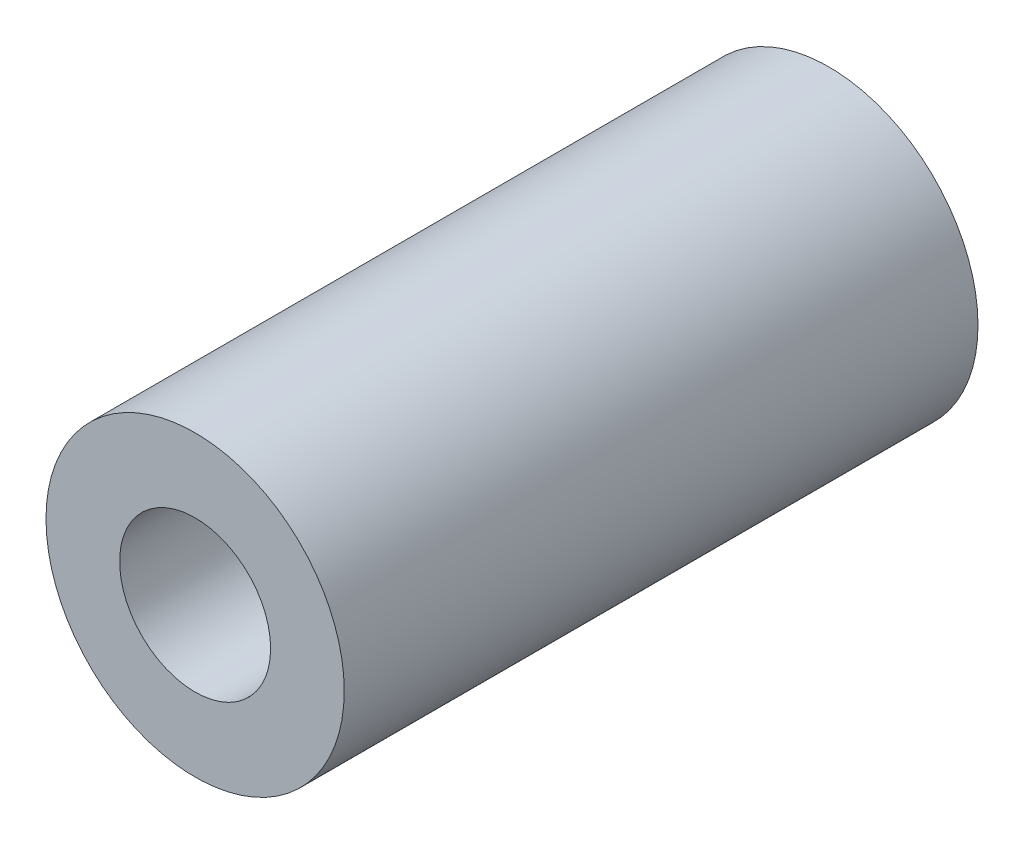
SolidWorks part; units mm, degrees
ref_plane "Front Plane" through (0, 0, 0) normal (0, 0, 1) x (1, 0, 0)
ref_plane "Top Plane" through (0, 0, 0) normal (0, 1, 0) x (1, 0, 0)
ref_plane "Right Plane" through (0, 0, 0) normal (1, 0, 0) x (0, 0, -1)
sketch "S01 - Solid post blank - 16 mm" plane through (0, 0, 0) normal (0, 0, 1) x (1, 0, 0)
  circle A0 centre (0, 0) radius 8
extrude "01 - Solid post blank - 16 mm" add sketch "S01 - Solid post blank - 16 mm" along normal blind 34
sketch "S02 - Rear M6 heat-set insert seat" plane through (0, 0, 0) normal (0, 0, 1) x (1, 0, 0)
  circle A0 centre (0, 0) radius 4.05
extrude "02 - Rear M6 heat-set insert seat" cut sketch "S02 - Rear M6 heat-set insert seat" along normal blind 14.35 from offset 0.1 offset against normal yes
sketch "S03 - Front M6 heat-set insert seat" plane through (0, 0, 0) normal (0, 0, 1) x (1, 0, 0)
  circle A0 centre (0, 0) radius 4.05
extrude "03 - Front M6 heat-set insert seat" cut sketch "S03 - Front M6 heat-set insert seat" along normal blind 14.35 from offset 19.75
